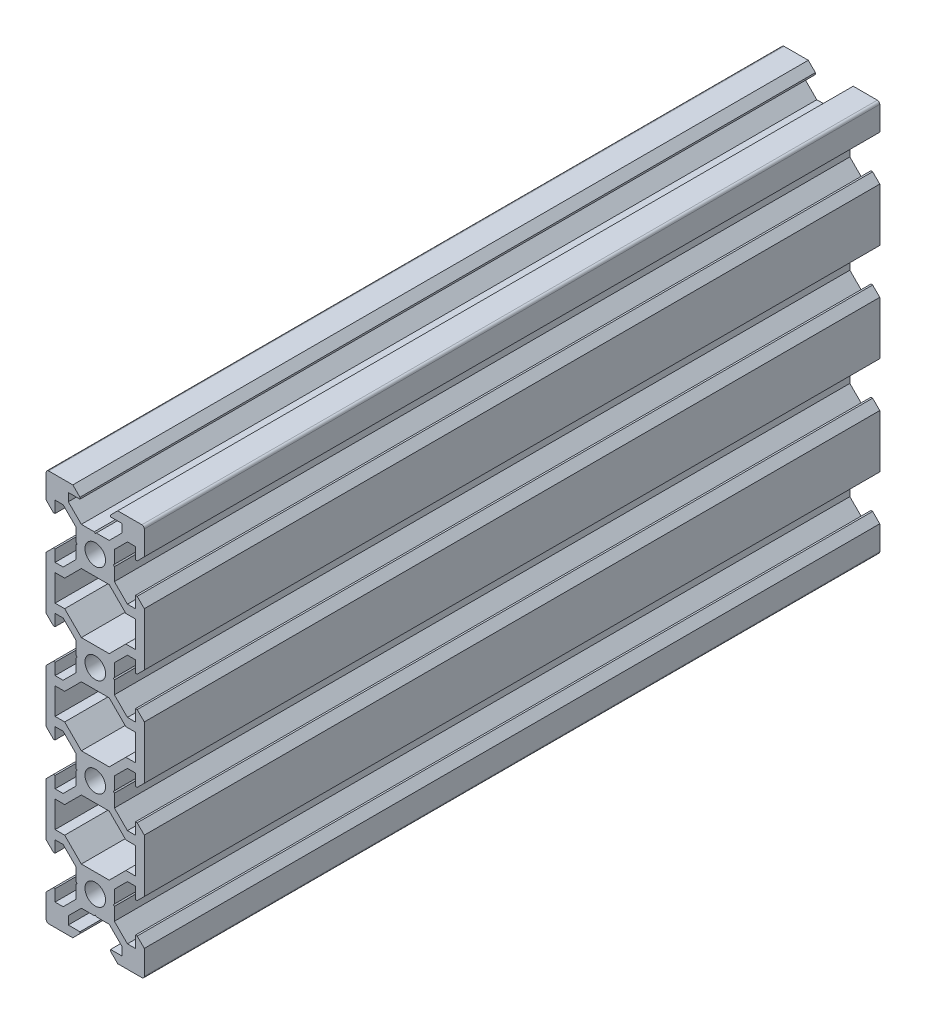
SolidWorks part; units mm, degrees
material "6061-T6 (SS)"
ref_plane "Front Plane" through (0, 0, 0) normal (0, 0, 1) x (1, 0, 0)
ref_plane "Top Plane" through (0, 0, 0) normal (0, 1, 0) x (1, 0, 0)
ref_plane "Right Plane" through (0, 0, 0) normal (1, 0, 0) x (0, 0, -1)
ref_plane "Plane1" through (0, 0, 500) normal (0, 0, 1) x (1, 0, 0)
sketch "Sketch1" plane through (0, 0, 500) normal (0, 0, 1) x (1, 0, 0)
  line L0 (6.5607, 24.5) -> (3.9, 27.1607)
  line L1 (3.9, 27.1607) -> (3.9, 29.79)
  line L2 (3.9, 29.79) -> (3.69, 30)
  line L3 (3.69, 30) -> (3.9, 30.21)
  line L4 (3.9, 30.21) -> (3.9, 32.8393)
  line L5 (3.9, 32.8393) -> (6.5607, 35.5)
  line L6 (6.5607, 35.5) -> (8.2, 35.5)
  line L7 (8.2, 35.5) -> (8.2, 33.125)
  line L8 (8.2, 33.125) -> (8.545, 33.125)
  line L9 (8.545, 33.125) -> (10, 34.58)
  line L10 (10, 34.58) -> (10, 39.5)
  line L11 (9.5, 40) -> (4.58, 40)
  line L12 (4.58, 40) -> (3.125, 38.545)
  line L13 (3.125, 38.545) -> (3.125, 38.2)
  line L14 (3.125, 38.2) -> (5.5, 38.2)
  line L15 (5.5, 38.2) -> (5.5, 36.5607)
  line L16 (5.5, 36.5607) -> (2.8393, 33.9)
  line L17 (2.8393, 33.9) -> (0.21, 33.9)
  line L18 (0.21, 33.9) -> (0, 33.69)
  line L19 (0, 33.69) -> (-0.21, 33.9)
  line L20 (-0.21, 33.9) -> (-2.8393, 33.9)
  line L21 (-2.8393, 33.9) -> (-5.5, 36.5607)
  line L22 (-5.5, 36.5607) -> (-5.5, 38.2)
  line L23 (-5.5, 38.2) -> (-3.125, 38.2)
  line L24 (-3.125, 38.2) -> (-3.125, 38.545)
  line L25 (-3.125, 38.545) -> (-4.58, 40)
  line L26 (-4.58, 40) -> (-9.5, 40)
  line L27 (-10, 39.5) -> (-10, 34.58)
  line L28 (-10, 34.58) -> (-8.545, 33.125)
  line L29 (-8.545, 33.125) -> (-8.2, 33.125)
  line L30 (-8.2, 33.125) -> (-8.2, 35.5)
  line L31 (-8.2, 35.5) -> (-6.5607, 35.5)
  line L32 (-6.5607, 35.5) -> (-3.9, 32.8393)
  line L33 (-3.9, 32.8393) -> (-3.9, 30.21)
  line L34 (-3.9, 30.21) -> (-3.69, 30)
  line L35 (-3.69, 30) -> (-3.9, 29.79)
  line L36 (-3.9, 29.79) -> (-3.9, 27.1607)
  line L37 (-3.9, 27.1607) -> (-6.5607, 24.5)
  line L38 (-6.5607, 24.5) -> (-8.2, 24.5)
  line L39 (-8.2, 24.5) -> (-8.2, 26.875)
  line L40 (-8.2, 26.875) -> (-8.545, 26.875)
  line L41 (-8.545, 26.875) -> (-10, 25.42)
  line L42 (-10, 25.42) -> (-10, 14.58)
  line L43 (-10, 14.58) -> (-8.545, 13.125)
  line L44 (-8.545, 13.125) -> (-8.2, 13.125)
  line L45 (-8.2, 13.125) -> (-8.2, 15.5)
  line L46 (-8.2, 15.5) -> (-6.5607, 15.5)
  line L47 (-6.5607, 15.5) -> (-3.9, 12.8393)
  line L48 (-3.9, 12.8393) -> (-3.9, 10.21)
  line L49 (-3.9, 10.21) -> (-3.69, 10)
  line L50 (-3.69, 10) -> (-3.9, 9.79)
  line L51 (-3.9, 9.79) -> (-3.9, 7.1607)
  line L52 (-3.9, 7.1607) -> (-6.5607, 4.5)
  line L53 (-6.5607, 4.5) -> (-8.2, 4.5)
  line L54 (-8.2, 4.5) -> (-8.2, 6.875)
  line L55 (-8.2, 6.875) -> (-8.545, 6.875)
  line L56 (-8.545, 6.875) -> (-10, 5.42)
  line L57 (-10, 5.42) -> (-10, -5.42)
  line L58 (-10, -5.42) -> (-8.545, -6.875)
  line L59 (-8.545, -6.875) -> (-8.2, -6.875)
  line L60 (-8.2, -6.875) -> (-8.2, -4.5)
  line L61 (-8.2, -4.5) -> (-6.5607, -4.5)
  line L62 (-6.5607, -4.5) -> (-3.9, -7.1607)
  line L63 (-3.9, -7.1607) -> (-3.9, -9.79)
  line L64 (-3.9, -9.79) -> (-3.69, -10)
  line L65 (-3.69, -10) -> (-3.9, -10.21)
  line L66 (-3.9, -10.21) -> (-3.9, -12.8393)
  line L67 (-3.9, -12.8393) -> (-6.5607, -15.5)
  line L68 (-6.5607, -15.5) -> (-8.2, -15.5)
  line L69 (-8.2, -15.5) -> (-8.2, -13.125)
  line L70 (-8.2, -13.125) -> (-8.545, -13.125)
  line L71 (-8.545, -13.125) -> (-10, -14.58)
  line L72 (-10, -14.58) -> (-10, -25.42)
  line L73 (-10, -25.42) -> (-8.545, -26.875)
  line L74 (-8.545, -26.875) -> (-8.2, -26.875)
  line L75 (-8.2, -26.875) -> (-8.2, -24.5)
  line L76 (-8.2, -24.5) -> (-6.5607, -24.5)
  line L77 (-6.5607, -24.5) -> (-3.9, -27.1607)
  line L78 (-3.9, -27.1607) -> (-3.9, -29.79)
  line L79 (-3.9, -29.79) -> (-3.69, -30)
  line L80 (-3.69, -30) -> (-3.9, -30.21)
  line L81 (-3.9, -30.21) -> (-3.9, -32.8393)
  line L82 (-3.9, -32.8393) -> (-6.5607, -35.5)
  line L83 (-6.5607, -35.5) -> (-8.2, -35.5)
  line L84 (-8.2, -35.5) -> (-8.2, -33.125)
  line L85 (-8.2, -33.125) -> (-8.545, -33.125)
  line L86 (-8.545, -33.125) -> (-10, -34.58)
  line L87 (-10, -34.58) -> (-10, -39.5)
  line L88 (-9.5, -40) -> (-4.58, -40)
  line L89 (-4.58, -40) -> (-3.125, -38.545)
  line L90 (-3.125, -38.545) -> (-3.125, -38.2)
  line L91 (-3.125, -38.2) -> (-5.5, -38.2)
  line L92 (-5.5, -38.2) -> (-5.5, -36.5607)
  line L93 (-5.5, -36.5607) -> (-2.8393, -33.9)
  line L94 (-2.8393, -33.9) -> (-0.21, -33.9)
  line L95 (-0.21, -33.9) -> (0, -33.69)
  line L96 (0, -33.69) -> (0.21, -33.9)
  line L97 (0.21, -33.9) -> (2.8393, -33.9)
  line L98 (2.8393, -33.9) -> (5.5, -36.5607)
  line L99 (5.5, -36.5607) -> (5.5, -38.2)
  line L100 (5.5, -38.2) -> (3.125, -38.2)
  line L101 (3.125, -38.2) -> (3.125, -38.545)
  line L102 (3.125, -38.545) -> (4.58, -40)
  line L103 (4.58, -40) -> (9.5, -40)
  line L104 (10, -39.5) -> (10, -34.58)
  line L105 (10, -34.58) -> (8.545, -33.125)
  line L106 (8.545, -33.125) -> (8.2, -33.125)
  line L107 (8.2, -33.125) -> (8.2, -35.5)
  line L108 (8.2, -35.5) -> (6.5607, -35.5)
  line L109 (6.5607, -35.5) -> (3.9, -32.8393)
  line L110 (3.9, -32.8393) -> (3.9, -30.21)
  line L111 (3.9, -30.21) -> (3.69, -30)
  line L112 (3.69, -30) -> (3.9, -29.79)
  line L113 (3.9, -29.79) -> (3.9, -27.1607)
  line L114 (3.9, -27.1607) -> (6.5607, -24.5)
  line L115 (6.5607, -24.5) -> (8.2, -24.5)
  line L116 (8.2, -24.5) -> (8.2, -26.875)
  line L117 (8.2, -26.875) -> (8.545, -26.875)
  line L118 (8.545, -26.875) -> (10, -25.42)
  line L119 (10, -25.42) -> (10, -14.58)
  line L120 (10, -14.58) -> (8.545, -13.125)
  line L121 (8.545, -13.125) -> (8.2, -13.125)
  line L122 (8.2, -13.125) -> (8.2, -15.5)
  line L123 (8.2, -15.5) -> (6.5607, -15.5)
  line L124 (6.5607, -15.5) -> (3.9, -12.8393)
  line L125 (3.9, -12.8393) -> (3.9, -10.21)
  line L126 (3.9, -10.21) -> (3.69, -10)
  line L127 (3.69, -10) -> (3.9, -9.79)
  line L128 (3.9, -9.79) -> (3.9, -7.1607)
  line L129 (3.9, -7.1607) -> (6.5607, -4.5)
  line L130 (6.5607, -4.5) -> (8.2, -4.5)
  line L131 (8.2, -4.5) -> (8.2, -6.875)
  line L132 (8.2, -6.875) -> (8.545, -6.875)
  line L133 (8.545, -6.875) -> (10, -5.42)
  line L134 (10, -5.42) -> (10, 5.42)
  line L135 (10, 5.42) -> (8.545, 6.875)
  line L136 (8.545, 6.875) -> (8.2, 6.875)
  line L137 (8.2, 6.875) -> (8.2, 4.5)
  line L138 (8.2, 4.5) -> (6.5607, 4.5)
  line L139 (6.5607, 4.5) -> (3.9, 7.1607)
  line L140 (3.9, 7.1607) -> (3.9, 9.79)
  line L141 (3.9, 9.79) -> (3.69, 10)
  line L142 (3.69, 10) -> (3.9, 10.21)
  line L143 (3.9, 10.21) -> (3.9, 12.8393)
  line L144 (3.9, 12.8393) -> (6.5607, 15.5)
  line L145 (6.5607, 15.5) -> (8.2, 15.5)
  line L146 (8.2, 15.5) -> (8.2, 13.125)
  line L147 (8.2, 13.125) -> (8.545, 13.125)
  line L148 (8.545, 13.125) -> (10, 14.58)
  line L149 (10, 14.58) -> (10, 25.42)
  line L150 (10, 25.42) -> (8.545, 26.875)
  line L151 (8.545, 26.875) -> (8.2, 26.875)
  line L152 (8.2, 26.875) -> (8.2, 24.5)
  line L153 (8.2, 24.5) -> (6.5607, 24.5)
  line L154 (2.8393, 13.9) -> (-2.8393, 13.9)
  line L155 (-2.8393, 13.9) -> (-6.2393, 17.3)
  line L156 (-6.2393, 17.3) -> (-8.2, 17.3)
  line L157 (-8.2, 17.3) -> (-8.2, 22.7)
  line L158 (-8.2, 22.7) -> (-6.2393, 22.7)
  line L159 (-6.2393, 22.7) -> (-2.8393, 26.1)
  line L160 (-2.8393, 26.1) -> (2.8393, 26.1)
  line L161 (2.8393, 26.1) -> (6.2393, 22.7)
  line L162 (6.2393, 22.7) -> (8.2, 22.7)
  line L163 (8.2, 22.7) -> (8.2, 17.3)
  line L164 (8.2, 17.3) -> (6.2393, 17.3)
  line L165 (6.2393, 17.3) -> (2.8393, 13.9)
  line L166 (2.8393, -6.1) -> (-2.8393, -6.1)
  line L167 (-2.8393, -6.1) -> (-6.2393, -2.7)
  line L168 (-6.2393, -2.7) -> (-8.2, -2.7)
  line L169 (-8.2, -2.7) -> (-8.2, 2.7)
  line L170 (-8.2, 2.7) -> (-6.2393, 2.7)
  line L171 (-6.2393, 2.7) -> (-2.8393, 6.1)
  line L172 (-2.8393, 6.1) -> (2.8393, 6.1)
  line L173 (2.8393, 6.1) -> (6.2393, 2.7)
  line L174 (6.2393, 2.7) -> (8.2, 2.7)
  line L175 (8.2, 2.7) -> (8.2, -2.7)
  line L176 (8.2, -2.7) -> (6.2393, -2.7)
  line L177 (6.2393, -2.7) -> (2.8393, -6.1)
  line L178 (2.8393, -26.1) -> (-2.8393, -26.1)
  line L179 (-2.8393, -26.1) -> (-6.2393, -22.7)
  line L180 (-6.2393, -22.7) -> (-8.2, -22.7)
  line L181 (-8.2, -22.7) -> (-8.2, -17.3)
  line L182 (-8.2, -17.3) -> (-6.2393, -17.3)
  line L183 (-6.2393, -17.3) -> (-2.8393, -13.9)
  line L184 (-2.8393, -13.9) -> (2.8393, -13.9)
  line L185 (2.8393, -13.9) -> (6.2393, -17.3)
  line L186 (6.2393, -17.3) -> (8.2, -17.3)
  line L187 (8.2, -17.3) -> (8.2, -22.7)
  line L188 (8.2, -22.7) -> (6.2393, -22.7)
  line L189 (6.2393, -22.7) -> (2.8393, -26.1)
  circle A0 centre (0, -10) radius 2.1
  circle A1 centre (0, 10) radius 2.1
  circle A2 centre (0, 30) radius 2.1
  circle A3 centre (0, -30) radius 2.1
  arc A4 (10, 39.5) -> (9.5, 40) centre (9.5, 39.5) ccw
  arc A5 (-9.5, 40) -> (-10, 39.5) centre (-9.5, 39.5) ccw
  arc A6 (-10, -39.5) -> (-9.5, -40) centre (-9.5, -39.5) ccw
  arc A7 (9.5, -40) -> (10, -39.5) centre (9.5, -39.5) ccw
extrude "Boss-Extrude1" add sketch "Sketch1" against normal blind 150
